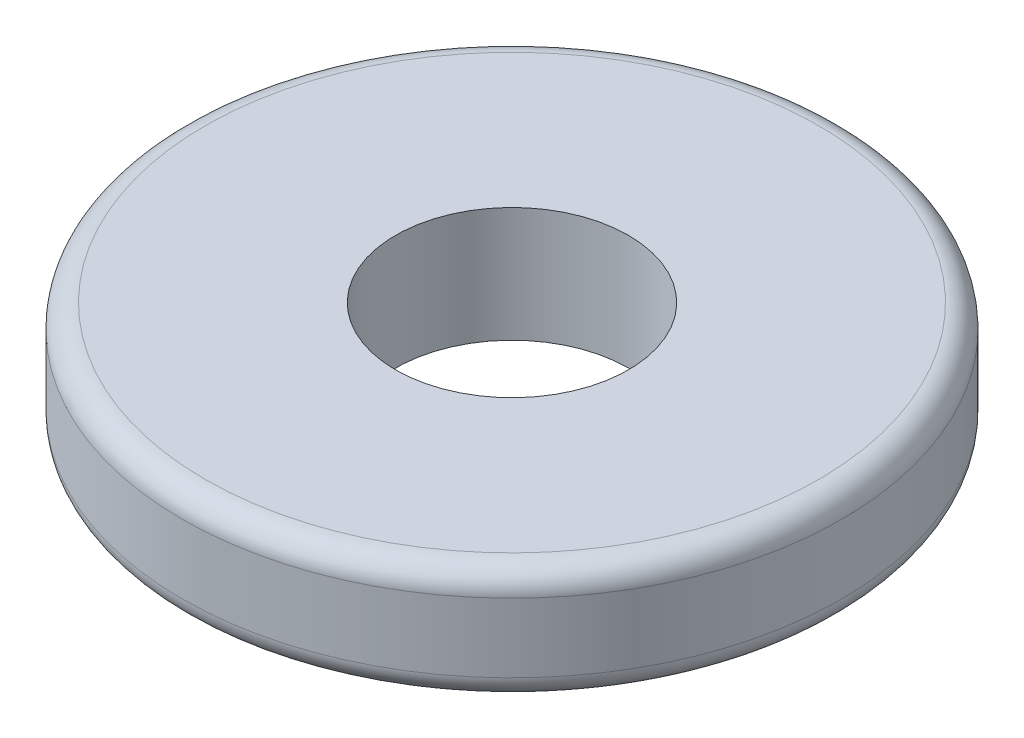
SolidWorks part; units mm, degrees
ref_plane "Спереди" through (0, 0, 0) normal (0, 0, 1) x (1, 0, 0)
ref_plane "Сверху" through (0, 0, 0) normal (0, 1, 0) x (1, 0, 0)
ref_plane "Справа" through (0, 0, 0) normal (1, 0, 0) x (0, 0, -1)
other "Configuration Table"
sketch "Sketch1" plane through (0, 0, 0) normal (0, 1, 0) x (1, 0, 0)
  circle A2 centre (0, 0) radius 1.52
  circle A3 centre (0, 0) radius 4.3
extrude "Boss-Extrude3" add sketch "Sketch1" along normal blind 1.5 contours A3 | A2
fillet "Fillet3" radius 0.3 2 edges at (0, 0, 4.3) (0, 1.5, 4.3)
